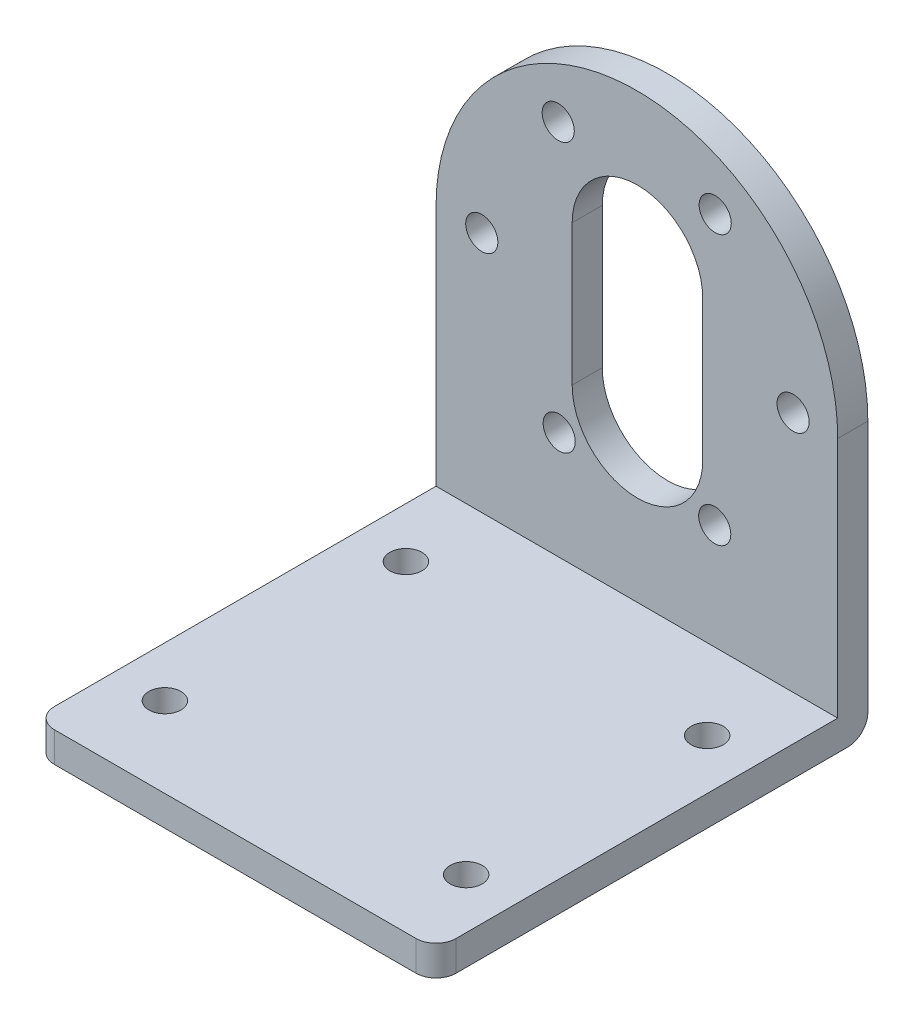
SolidWorks part; units mm, degrees
material "5052-H32"
ref_plane "前视基准面" through (0, 0, 0) normal (0, 0, 1) x (1, 0, 0)
ref_plane "上视基准面" through (0, 0, 0) normal (0, 1, 0) x (1, 0, 0)
ref_plane "右视基准面" through (0, 0, 0) normal (1, 0, 0) x (0, 0, -1)
sketch "草图1" plane through (0, 0, 0) normal (0, 0, 1) x (1, 0, 0)
  line L0 (-17.2131, -8.0912) -> (22.7869, -8.0912)
  line L5 (-17.2131, -8.0912) -> (-17.2131, 18.9088)
  line L6 (22.7869, -8.0912) -> (22.7869, 18.9088)
  line L7 (-17.2131, -8.0912) -> (-17.2131, -5.204)
  line L12 (-17.2131, -5.204) -> (22.7869, -5.204)
  line L15 (-3.6567, 10.296) -> (-3.6567, 24.296)
  line L16 (9.3433, 10.296) -> (9.3433, 24.296)
  arc A2 (-17.2131, 18.9088) -> (22.7869, 18.9088) centre (2.7869, 18.9088) cw
  arc A3 (-3.6567, 10.296) -> (9.3433, 10.296) centre (2.8433, 10.296) ccw
  arc A4 (9.3433, 24.296) -> (-3.6567, 24.296) centre (2.8433, 24.296) ccw
  circle A6 centre (-12.6567, 18.9088) radius 1.6
  circle A7 centre (18.3433, 18.9088) radius 1.6
  circle A8 centre (-5.0458, 32.2975) radius 1.6
  circle A9 centre (10.5868, 32.1606) radius 1.6
  circle A10 centre (10.5392, 5.3198) radius 1.6
  circle A11 centre (-4.9476, 5.5574) radius 1.6
  point P15 (0, 0)
  point P18 (0, 0)
  point P19 (0, 0)
  point P29 (0, 0)
extrude "凸台-拉伸4" add sketch "草图1" along normal blind 3 contours A2 L5 L12 L6 A11 A10 A9 A8 A7 A6 A4 L16 A3 L15
sketch "草图2" plane through (0, 0, 0) normal (0, 0, 1) x (1, 0, 0)
  line L0 (22.7869, -5.204) -> (22.7869, -8.204)
  line L1 (22.7869, -8.204) -> (-17.2131, -8.204)
  line L2 (-17.2131, -8.204) -> (-17.2131, -5.204)
  line L3 (22.7869, -5.204) -> (-17.2131, -5.204)
extrude "凸台-拉伸5" add sketch "草图2" along normal blind 43
sketch "草图3" plane through (0, 0, 0) normal (0, 1, 0) x (1, 0, 0)
  line L0 (-17.2131, -43) -> (-12.2131, -43)
  line L1 (-17.2131, -43) -> (22.7869, -43) construction
  circle A0 centre (-12.2131, -35) radius 1.6
  circle A1 centre (-12.2131, -11) radius 1.6
  circle A2 centre (17.7869, -35) radius 1.6
  circle A3 centre (17.7869, -11) radius 1.6
extrude "切除-拉伸1" cut sketch "草图3" against normal through all contours A0 | A2 | A3 | A1
fillet "圆角5" radius 2 1 edges at (22.7869, -6.704, 43)
fillet "圆角6" radius 2 1 edges at (-17.2131, -6.704, 43)
fillet "圆角7" radius 2 1 edges at (2.7869, -8.204, 0)
